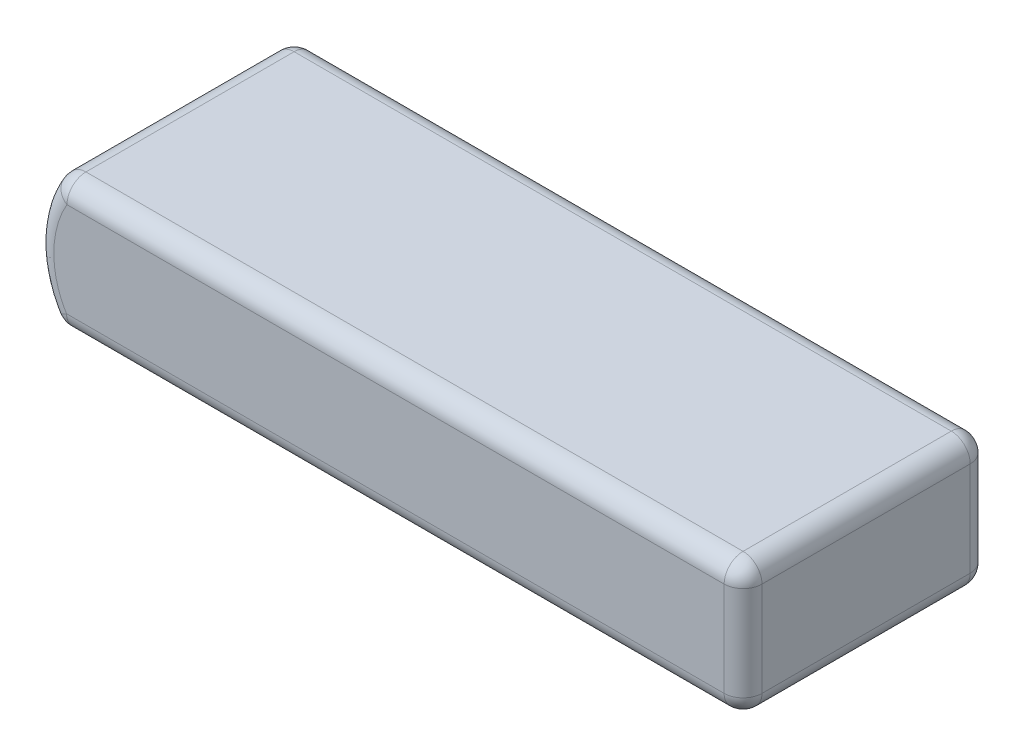
SolidWorks part; units mm, degrees
material "ASTM A36 Steel"
ref_plane "Front Plane" through (0, 0, 0) normal (0, 0, 1) x (1, 0, 0)
ref_plane "Top Plane" through (0, 0, 0) normal (0, 1, 0) x (1, 0, 0)
ref_plane "Right Plane" through (0, 0, 0) normal (1, 0, 0) x (0, 0, -1)
sketch "Sketch1" plane through (0, 0, 0) normal (0, 1, 0) x (1, 0, 0)
  line L1 (-72.5, 26) -> (72.5, 26)
  line L2 (-72.5, 26) -> (-72.5, -26)
  line L3 (-72.5, -26) -> (72.5, -26)
  line L4 (72.5, 26) -> (72.5, -26)
  line L5 (-72.5, 26) -> (72.5, -26) construction
  line L6 (-72.5, -26) -> (72.5, 26) construction
  point P0 (0, 0)
  dimension "D1" = 145
  dimension "D2" = 52
extrude "Boss-Extrude1" add sketch "Sketch1" along normal blind 28
sketch "Sketch2" plane through (0, 0, 26) normal (0, 0, 1) x (1, 0, 0)
  line L0 (-72.5, 28) -> (-72.5, 0)
  spline S0 degree 3 poles (-72.5, 28) (-78.4932, 20.0257) (-78.9104, 7.8896) (-72.5, 0) knots 0 0 0 0 1 1 1 1
  dimension "D1" = 4
  dimension "D2" = 4
extrude "Boss-Extrude2" add sketch "Sketch2" against normal blind 52
fillet "Fillet1" radius 4 12 edges at (0, 0, -26) (-72.5, 0, 0) (0, 0, 26) (72.5, 0, 0) (0, 28, 26) (-72.5, 28, 0) (0, 28, -26) (72.5, 28, 0) (72.5, 14, -26) (72.5, 14, 26)
